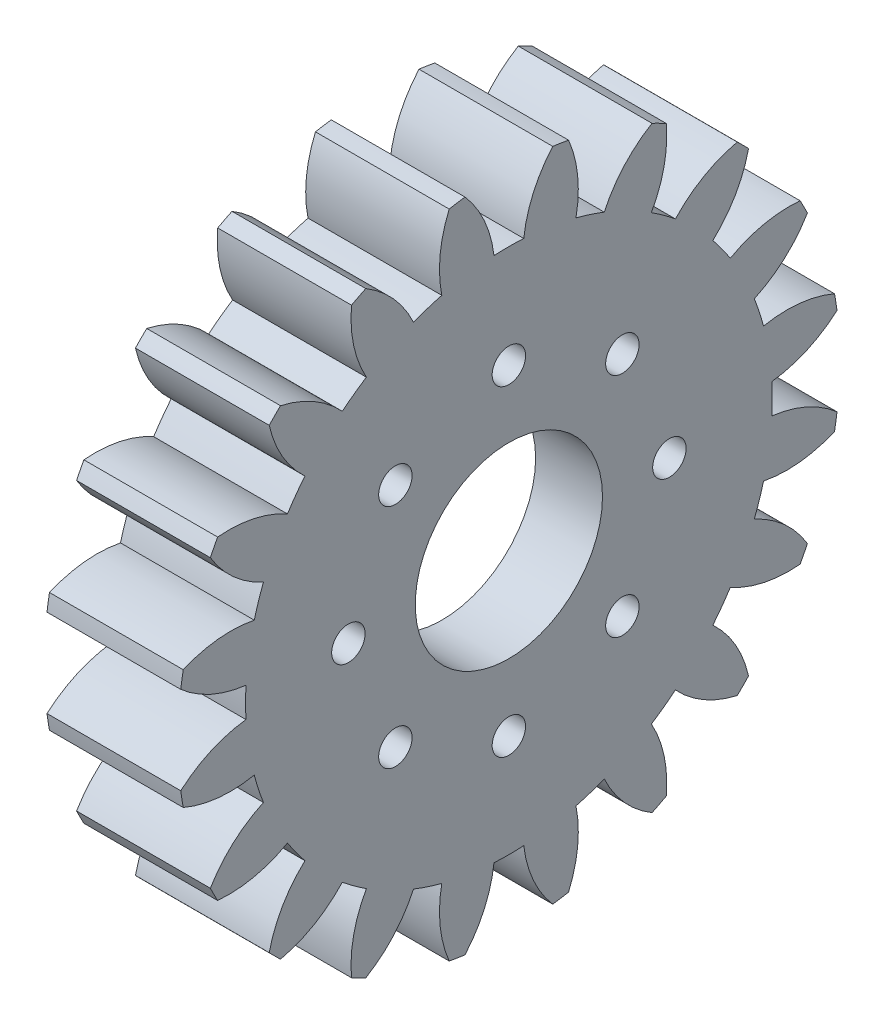
SolidWorks part; units mm, degrees
ref_plane "Plane1" through (0, 0, 0) normal (0, 0, 1) x (1, 0, 0)
ref_plane "Plane2" through (0, 0, 0) normal (0, 1, 0) x (1, 0, 0)
ref_plane "Plane3" through (0, 0, 0) normal (1, 0, 0) x (0, 0, -1)
sketch "HoldingSke" plane through (0, 0, 0) normal (0, 1, 0) x (1, 0, 0)
  line L0 (0, 0) -> (0.4176, -0.152)
  line L1 (-15, 0) -> (100, 0) construction
  line L2 (0, 0) -> (-2.1039, 2.3779)
  line L3 (0, 0) -> (-11.863, 4.5341)
  line L4 (0, 0) -> (8.1152, 2.9537)
  line L5 (0, 0) -> (-46.8476, -17.4728)
  line L6 (0, 0) -> (-8.2896, -5.593)
  line L7 (-2.1039, 2.3779) -> (8.6586, 51.2059)
  line L8 (-76.2, 54.61) -> (-72.9, 54.61)
  line L9 (-71.009, 38.7566) -> (-53.1078, 45.2721)
  line L10 (-76.2, 71.12) -> (104.1128, 71.12)
  line L11 (0, 0) -> (-10, 0)
  line L12 (-76.2, 101.6) -> (-76.123, 101.6)
  line L13 (24.9733, 27.94) -> (52.9518, 28.4284)
  line L14 (24.9733, 27.94) -> (24.9743, 27.94)
  line L15 (24.9733, 27.94) -> (100.4006, 29.5858)
  line L16 (-63.627, -2.25) -> (-12.827, -2.25)
  circle A0 centre (0, 0) radius 15
  circle A1 centre (0, 0) radius 19.6865
  circle A2 centre (0, 0) radius 37.5
  circle A3 centre (0, 0) radius 15
  dimension "MHD" = 39.373
  dimension "Hub_dia" = 75
  dimension "Bore" = 30
  dimension "MBD" = 30
  dimension "Num_teeth" = 20
  dimension "Pitch" = 0.4444
  dimension "Overall_len" = 50
  dimension "Show_teeth" = 20
  dimension "Thickness" = 10
  dimension "OAL" = 50.0001
  dimension "T_dim" = 3.3
  dimension "Ap" = 20
  dimension "H" = 19.05
  dimension "Pitch_radius" = 180.3128
  dimension "Width" = 10
  dimension "Backlash" = 0.077
  dimension "Addendum_fac" = 1
  dimension "Dedendum_fac" = 1.25
  dimension "Clearance_fac" = 0.25
  dimension "Dedendum_add" = 0.001
  dimension "Module" = 2.25
sketch "BasProSke" plane through (0, 0, 0) normal (0, 1, 0) x (1, 0, 0)
  line L0 (-10, 0) -> (60, 0) construction
  line L1 (0, 0) -> (0, 24.75)
  line L2 (0, 0) -> (10, 0)
  line L3 (10, 0) -> (10, 24.75)
  line L4 (10, 24.75) -> (0, 24.75)
  dimension "Thickness" = 10
  dimension "Diameter" = 49.5
revolve "Base-Revolve" add sketch "BasProSke" angle 360 about L0
sketch "TooCutSke" plane through (0, 0, 0) normal (1, 0, 0) x (0, 0, -1)
  line L1 (0, 0) -> (0, 107) construction
  line L2 (0, 0) -> (-1.9, 22.4196) construction
  line L3 (0, 0) -> (-7.021, 44.3291) construction
  line L4 (-1.9, 22.4196) -> (-3.5105, 22.1646) construction
  arc A0 (1.1119, 19.6551) -> (-1.1119, 19.6551) centre (0, 0) ccw
  arc A1 (3.3, 24.5546) -> (-3.3, 24.5546) centre (0, 0) ccw
  circle A2 centre (0, 0) radius 22.5 construction
  circle A3 centre (0, 0) radius 21.1431 construction
  arc A4 (-1.1119, 19.6551) -> (-3.3, 24.5546) centre (-10.0501, 18.6018) ccw
  arc A5 (3.3, 24.5546) -> (1.1119, 19.6551) centre (10.0501, 18.6018) ccw
  dimension "Root_dia" = 39.373
  dimension "Overcut_dia" = 49.5508
  dimension "Pitch_dia" = 45
  dimension "Base_dia" = 42.2862
  dimension "Flank_rad" = 9
  dimension "Half_ang" = 9
  dimension "Half_CT" = 1.6306
extrude "ToothCut" cut sketch "TooCutSke" along normal through all
fillet "Breaks" [suppressed] radius 0.045
fillet "RootFillets" [suppressed] radius 0.5635
pattern_circular "TeethCuts" count 20 every 18 about axis through (-10, 0, 0) along (1, 0, 0) of "ToothCut", "RootFillets", "Breaks"
sketch "HubNeaOneSke" plane through (0, 0, 0) normal (-1, 0, 0) x (0, 0, 1)
  circle A0 centre (0, 0) radius 19.6865
  dimension "Diameter" = 39.373
extrude "HubNearOne" [suppressed] add sketch "HubNeaOneSke" along normal blind 40.0001
sketch "HubNeaBotSke" plane through (0, 0, 0) normal (-1, 0, 0) x (0, 0, 1)
  circle A0 centre (0, 0) radius 19.6865
  dimension "Diameter" = 39.373
extrude "HubNearBoth" [suppressed] add sketch "HubNeaBotSke" along normal blind 20
ref_plane "FarPln" through (10, 0, 0) normal (1, 0, 0) x (0, 0, -1)
sketch "HubFarSke" plane through (10, 0, 0) normal (1, 0, 0) x (0, 0, -1)
  circle A0 centre (0, 0) radius 19.6865
  dimension "Diameter" = 39.373
extrude "HubFar" [suppressed] add sketch "HubFarSke" along normal blind 20
sketch "BorSke" plane through (0, 0, 0) normal (1, 0, 0) x (0, 0, -1)
  circle A0 centre (0, 0) radius 15
  dimension "Diameter" = 30
extrude "Bore" cut sketch "BorSke" along normal mid plane 100.0001
sketch "KeySke" plane through (0, 0, 0) normal (1, 0, 0) x (0, 0, -1)
  line L0 (-5, 0) -> (-5, 18.3)
  line L1 (-5, 18.3) -> (5, 18.3)
  line L2 (5, 18.3) -> (5, 0)
  line L3 (0, 0) -> (0, 34) construction
  line L4 (-5, 0) -> (5, 0)
  dimension "Width" = 10
  dimension "Offset" = 18.3
extrude "Keyway" [suppressed] cut sketch "KeySke" along normal mid plane 100.0001
pattern_circular "Keyway2" [suppressed] count 2 every 90 about axis through (-10, 0, 0) along (1, 0, 0)
sketch "Sketch1" plane through (10, 0, 0) normal (1, 0, 0) x (0, 0, -1)
  circle A0 centre (0, 0) radius 15
extrude "Boss-Extrude1" add sketch "Sketch1" against normal blind 5
sketch "Sketch2" plane through (10, 0, 0) normal (1, 0, 0) x (0, 0, -1)
  circle A0 centre (0, 0) radius 7
  dimension "D1" = 14
extrude "Cut-Extrude1" cut sketch "Sketch2" against normal blind 5
sketch "Sketch3" plane through (10, 0, 0) normal (1, 0, 0) x (0, 0, -1)
  circle A1 centre (0, 12) radius 1.25
  circle A2 centre (8.4853, 8.4853) radius 1.25
  circle A3 centre (12, 0) radius 1.25
  circle A4 centre (8.4853, -8.4853) radius 1.25
  circle A5 centre (0, -12) radius 1.25
  circle A6 centre (-8.4853, -8.4853) radius 1.25
  circle A7 centre (-12, 0) radius 1.25
  circle A8 centre (-8.4853, 8.4853) radius 1.25
  point P21 (0, 0)
  dimension "D2" = 2.5
  dimension "D3" = 8
extrude "Cut-Extrude2" cut sketch "Sketch3" against normal blind 5
equation "' \"Module@HoldingSke\" = 6.35"
equation "' \"Num_teeth@HoldingSke\" = 12"
equation "' \"Ap@HoldingSke\" =  20"
equation "' \"Ap@HoldingSke\" = 20"
equation "' \"Width@HoldingSke\" = 0.5 * 25.4"
equation "' \"Hub_dia@HoldingSke\"= 1 * 25.4"
equation "' \"Hub_dia@HoldingSke\" = 1 * 25.4"
equation "' \"Overall_len@HoldingSke\" = 1.0 * 25.4"
equation "' \"Bore@HoldingSke\" = 0.75 * 25.4"
equation "' \"T_dim@HoldingSke\" = 0.1 * 25.4"
equation "' \"Width@KeySke\" = 0.25 * 25.4"
equation "' \"Show_teeth@HoldingSke\" = 13"
equation "' \"Backlash@HoldingSke\" = 0.009 * 25.4"
equation "' \"Addendum_fac@HoldingSke\" = 1.0"
equation "' \"Dedendum_fac@HoldingSke\" = 1.25"
equation "' \"Dedendum_add@HoldingSke\" = 0.00005 * 25.4"
equation "' \"Clearance_fac@HoldingSke\" = 0.25"
equation "\"Pitch@HoldingSke\" = 1 / \"Module@HoldingSke\""
equation "\"Overcut_dia@TooCutSke\" = (\"Num_teeth@HoldingSke\" + 2 * \"Addendum_fac@HoldingSke\") / \"Pitch@HoldingSke\" + 0.002 * 25.4"
equation "\"Pitch_dia@TooCutSke\" = \"Num_teeth@HoldingSke\" / \"Pitch@HoldingSke\""
equation "\"Base_dia@TooCutSke\" = \"Num_teeth@HoldingSke\" / \"Pitch@HoldingSke\" * cos((\"Ap@HoldingSke\"  * 3.14159265 / 180))"
equation "\"Root_dia@TooCutSke\" = (\"Num_teeth@HoldingSke\" + 2) / \"Pitch@HoldingSke\" - 2 * (\"Addendum_fac@HoldingSke\" + \"Dedendum_fac@HoldingSke\") / \"Pitch@HoldingSke\" - \"Dedendum_add@HoldingSke\" * 2"
equation "\"Half_ang@TooCutSke\" = 180 / \"Num_teeth@HoldingSke\""
equation "\"Half_CT@TooCutSke\" = \"Num_teeth@HoldingSke\" / \"Pitch@HoldingSke\" * sin((3.14159265 / 2 / \"Num_teeth@HoldingSke\")) / 2 - 7 * \"Backlash@HoldingSke\" / 4"
equation "\"Flank_rad@TooCutSke\" = \"Num_teeth@HoldingSke\" / \"Pitch@HoldingSke\" / 5"
equation "\"Radius@RootFillets\" = \"Clearance_fac@HoldingSke\" / \"Pitch@HoldingSke\" + \"Dedendum_add@HoldingSke\""
equation "\"Break_rad@Breaks\" = 0.02 / \"Pitch@HoldingSke\""
equation "\"Thickness@HoldingSke\" = \"Width@HoldingSke\""
equation "\"OAL@HoldingSke\" = \"Thickness@HoldingSke\""
equation "\"MHD@HoldingSke\" = (\"Num_teeth@HoldingSke\" + 2) / \"Pitch@HoldingSke\" - 2 * (\"Addendum_fac@HoldingSke\" + \"Dedendum_fac@HoldingSke\")  / \"Pitch@HoldingSke\" - \"Dedendum_add@HoldingSke\" * 2"
equation "\"MBD@HoldingSke\" = (\"Num_teeth@HoldingSke\" + 2) / \"Pitch@HoldingSke\" - 2 * (\"Addendum_fac@HoldingSke\" + \"Dedendum_fac@HoldingSke\")  / \"Pitch@HoldingSke\" - \"Dedendum_add@HoldingSke\" * 2 - 0.002 * 25.4"
equation "\"MHD@HoldingSke\" = ((sgn( \"MHD@HoldingSke\" - \"Hub_dia@HoldingSke\" )-1)*( \"MHD@HoldingSke\" - \"Hub_dia@HoldingSke\" ))/-2+ \"Hub_dia@HoldingSke\""
equation "\"MBD@HoldingSke\" = ((sgn( \"MBD@HoldingSke\" - \"Bore@HoldingSke\" )-1)*( \"MBD@HoldingSke\" - \"Bore@HoldingSke\" ))/-2+ \"Bore@HoldingSke\""
equation "\"OAL@HoldingSke\" = ((sgn( \"OAL@HoldingSke\" - \"Overall_len@HoldingSke\" )+1)*( \"OAL@HoldingSke\" - \"Overall_len@HoldingSke\" ))/2 + \"Overall_len@HoldingSke\" + 0.000002 * 25.4"
equation "\"Num_teeth@TeethCuts\" = int( \"Show_teeth@HoldingSke\" ) + 1"
equation "\"Num_teeth@TeethCuts\" = ((sgn( \"Num_teeth@TeethCuts\" - \"Num_teeth@HoldingSke\" )-1)*( \"Num_teeth@TeethCuts\" - \"Num_teeth@HoldingSke\" ))/-2+ \"Num_teeth@HoldingSke\""
equation "\"Num_teeth@TeethCuts\" = ((sgn( \"Num_teeth@TeethCuts\" - 2.0)+1)*( \"Num_teeth@TeethCuts\" - 2.0))/2 +2.0"
equation "\"Angle@TeethCuts\" = 360.0 / \"Num_teeth@HoldingSke\""
equation "\"Diameter@BasProSke\" = (\"Num_teeth@HoldingSke\" + 2 * \"Addendum_fac@HoldingSke\") / \"Pitch@HoldingSke\""
equation "\"Thickness@BasProSke\"  = \"Thickness@HoldingSke\""
equation "' \"Fillet_rad@BasProSke\" =  \"Thickness@HoldingSke\" * 0.05"
equation "' \"Fillet_rad@BasProSke\" = \"Thickness@HoldingSke\" * 0.05"
equation "\"MHD@HoldingSke\" = ((sgn( \"MHD@HoldingSke\" - \"Root_dia@TooCutSke\" )-1)*( \"MHD@HoldingSke\" - \"Root_dia@TooCutSke\" ))/-2+ \"Root_dia@TooCutSke\""
equation "\"Diameter@HubNeaOneSke\" = \"MHD@HoldingSke\""
equation "\"Length@HubNearOne\" = \"OAL@HoldingSke\" - \"Thickness@BasProSke\""
equation "\"Diameter@HubNeaBotSke\" = \"MHD@HoldingSke\""
equation "\"Length@HubNearBoth\" = ( \"OAL@HoldingSke\" - \"Thickness@BasProSke\" ) / 2.0"
equation "\"Thickness@FarPln\" = \"Thickness@BasProSke\""
equation "\"Diameter@HubFarSke\" = \"MHD@HoldingSke\""
equation "\"Length@HubFar\" = ( \"OAL@HoldingSke\" - \"Thickness@BasProSke\" ) / 2.0"
equation "\"Diameter@BorSke\" = \"MBD@HoldingSke\""
equation "\"D1@Bore\" = \"OAL@HoldingSke\" * 2.0"
equation "\"D1@Keyway\" = \"OAL@HoldingSke\" * 2.0"
equation "\"Offset@KeySke\" = \"T_dim@HoldingSke\" + \"MBD@HoldingSke\" / 2.0"
